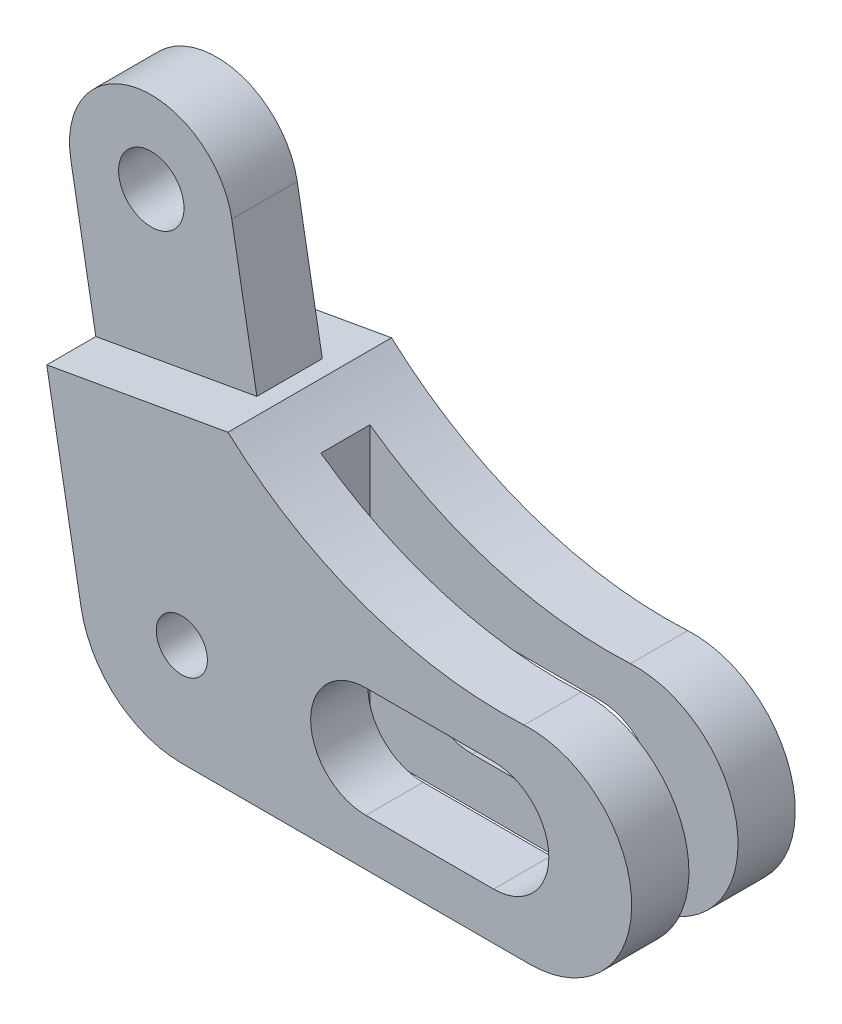
SolidWorks part; units mm, degrees
ref_plane "Front Plane" through (0, 0, 0) normal (0, 0, 1) x (1, 0, 0)
ref_plane "Top Plane" through (0, 0, 0) normal (0, 1, 0) x (1, 0, 0)
ref_plane "Right Plane" through (0, 0, 0) normal (1, 0, 0) x (0, 0, -1)
sketch "Sketch1" plane through (0, 0, 0) normal (0, 0, 1) x (1, 0, 0)
  line L0 (0, 31.8688) -> (0, -49.9621) construction
  line L1 (0, -13.9791) -> (85, -13.9791) construction
  line L2 (0, -38.9791) -> (85, -38.9791)
  line L3 (11.2814, 36.7824) -> (-33.0226, 28.8987)
  line L4 (-33.0226, 28.8987) -> (-24.6134, -18.359)
  line L5 (45, -13.9791) -> (76.2391, -13.9791) construction
  line L6 (45, -0.4791) -> (76.2391, -0.4791)
  line L7 (45, -27.4791) -> (76.2391, -27.4791)
  line L8 (-10.8706, 32.8405) -> (0, -7.7291) construction
  arc A0 (85, -38.9791) -> (83.6935, 10.9867) centre (85, -13.9791) ccw
  arc A1 (83.6935, 10.9867) -> (11.2814, 36.7824) centre (78.4675, 110.8501) cw
  arc A2 (-24.6134, -18.359) -> (0, -38.9791) centre (0, -13.9791) ccw
  circle A3 centre (0, -13.9791) radius 6.25
  arc A4 (45, -0.4791) -> (45, -27.4791) centre (45, -13.9791) ccw
  arc A5 (76.2391, -27.4791) -> (76.2391, -0.4791) centre (76.2391, -13.9791) ccw
  point P16 (60.6196, -13.9791)
  dimension "D3" = 13.5
  dimension "D4" = 25
  dimension "D5" = 100
  dimension "D7" = 12.5
  dimension "D10" = 25
  dimension "D1" = 45
  dimension "D2" = 40
  dimension "D6" = 48
  dimension "D8" = 45
  dimension "D9" = 15
extrude "Boss-Extrude1" add sketch "Sketch1" along normal mid plane 40
sketch "Sketch5" plane through (0, 0, 0) normal (0, 0, 1) x (1, 0, 0)
  line L0 (20, 29.7233) -> (20, -38.9791)
  line L1 (0, -38.9791) -> (85, -38.9791) construction
  line L2 (20, -38.9791) -> (85, -38.9791)
  arc A0 (11.2814, 36.7824) -> (83.6935, 10.9867) centre (78.4675, 110.8501) ccw construction
  arc A1 (20, 29.7233) -> (83.6935, 10.9867) centre (78.4675, 110.8501) ccw
  arc A2 (45, -0.4791) -> (45, -27.4791) centre (45, -13.9791) ccw construction
  arc A3 (45, -0.4791) -> (45, -27.4791) centre (45, -13.9791) ccw
  arc A4 (85, -38.9791) -> (83.6935, 10.9867) centre (85, -13.9791) ccw construction
  arc A5 (85, -38.9791) -> (83.6935, 10.9867) centre (85, -13.9791) ccw
  dimension "D1" = 25
extrude "Cut-Extrude2" cut sketch "Sketch5" against normal mid plane 12 contours A1 A5 L2 L0
sketch "Sketch7" plane through (0, 0, 0) normal (0, 0, 1) x (1, 0, 0)
  line L0 (11.2814, 36.7824) -> (-33.0226, 28.8987) construction
  line L1 (11.2814, 36.7824) -> (-33.0226, 28.8987)
  line L2 (-33.0226, 28.8987) -> (-39.1544, 63.3574)
  line L3 (-39.1544, 63.3574) -> (0.227, 70.3651)
  line L4 (0.227, 70.3651) -> (6.3587, 35.9064)
  circle A0 centre (-19.4637, 66.8612) radius 20
  point P7 (-11.5314, 68.2728)
  dimension "D2" = 40
  dimension "D1" = 35
extrude "Boss-Extrude2" add sketch "Sketch7" along normal blind 8 and the other way blind 8 contours A0 L2 L1 L4 | L3 A0 | L3 A0
sketch "Sketch8" plane through (0, 0, 8) normal (0, 0, 1) x (1, 0, 0)
  circle A0 centre (-19.4637, 66.8612) radius 8
  dimension "D1" = 16
extrude "Cut-Extrude3" cut sketch "Sketch8" against normal through all
